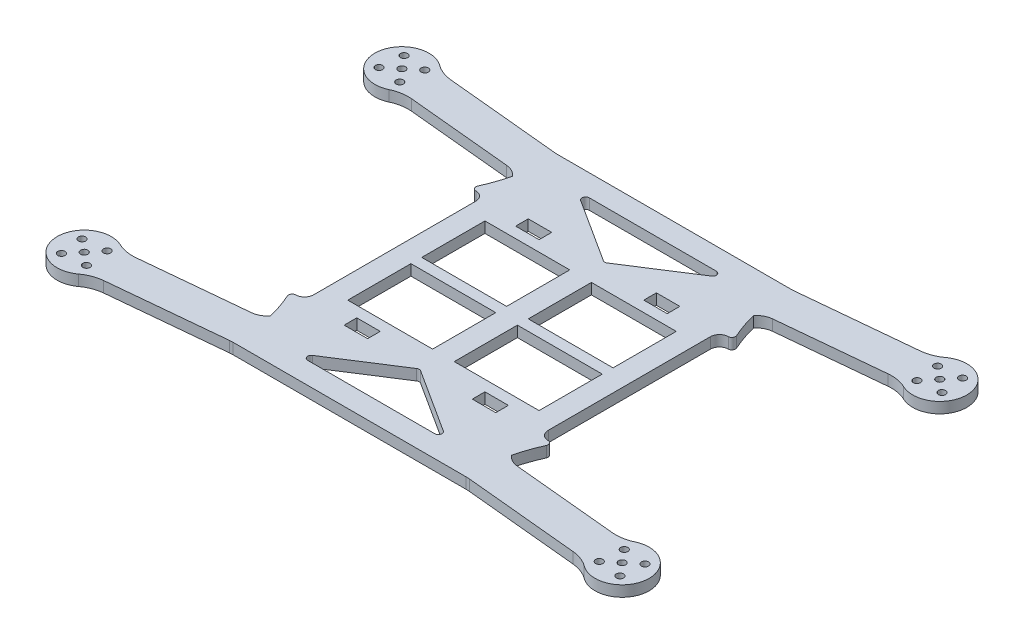
SolidWorks part; units mm, degrees
material "Custom PLA"
ref_plane "Front Plane" through (0, 0, 0) normal (0, 0, 1) x (1, 0, 0)
ref_plane "Top Plane" through (0, 0, 0) normal (0, 1, 0) x (1, 0, 0)
ref_plane "Right Plane" through (0, 0, 0) normal (1, 0, 0) x (0, 0, -1)
sketch "Sketch1" plane through (0, 0, 0) normal (0, 1, 0) x (1, 0, 0)
  line L0 (-101.3207, 0) -> (4964.7124, 0) construction
  line L1 (0, -101.3207) -> (0, 4964.7124) construction
  line L4 (33.2085, 45.046) -> (65.0466, 48.1117)
  line L5 (36.823, 35.3478) -> (66.0089, 38.1581)
  line L6 (0.5402, 25.8595) -> (18.1402, 37.1585)
  line L7 (3, 1.5) -> (26.5, 1.5)
  line L8 (3, 1.5) -> (3, 19)
  line L9 (3, 19) -> (26.5, 19)
  line L10 (26.5, 1.5) -> (26.5, 19)
  line L11 (14.5, 22) -> (21, 22)
  line L12 (14.5, 22) -> (14.5, 25.5)
  line L13 (14.5, 25.5) -> (21, 25.5)
  line L14 (21, 22) -> (21, 25.5)
  line L15 (17.6, 39) -> (-17.6, 39)
  line L16 (-18.1402, 37.1585) -> (-0.5402, 25.8595)
  line L17 (71.6376, 40.5277) -> (71.0277, 46.8624) construction
  line L18 (32.5, 22.45) -> (32.5, -22.45)
  line L30 (32.25, 45) -> (-32.25, 45)
  line L31 (-71.6376, 40.5277) -> (-71.0277, 46.8624) construction
  line L33 (-32.5, 22.45) -> (-32.5, -22.45)
  line L34 (-21, 22) -> (-21, 25.5)
  line L35 (-14.5, 25.5) -> (-21, 25.5)
  line L36 (-14.5, 22) -> (-14.5, 25.5)
  line L37 (-14.5, 22) -> (-21, 22)
  line L38 (-26.5, 1.5) -> (-26.5, 19)
  line L39 (-3, 19) -> (-26.5, 19)
  line L40 (-3, 1.5) -> (-3, 19)
  line L41 (-3, 1.5) -> (-26.5, 1.5)
  line L42 (-36.823, 35.3478) -> (-66.0089, 38.1581)
  line L43 (-33.2085, 45.046) -> (-65.0466, 48.1117)
  line L44 (-71.6376, -40.5277) -> (-71.0277, -46.8624) construction
  line L45 (71.6376, -40.5277) -> (71.0277, -46.8624) construction
  line L46 (-33.2085, -45.046) -> (-65.0466, -48.1117)
  line L47 (-36.823, -35.3478) -> (-66.0089, -38.1581)
  line L48 (-3, -1.5) -> (-26.5, -1.5)
  line L49 (-3, -1.5) -> (-3, -19)
  line L50 (-3, -19) -> (-26.5, -19)
  line L51 (-26.5, -1.5) -> (-26.5, -19)
  line L52 (-14.5, -22) -> (-21, -22)
  line L53 (-14.5, -22) -> (-14.5, -25.5)
  line L54 (-14.5, -25.5) -> (-21, -25.5)
  line L55 (-21, -22) -> (-21, -25.5)
  line L56 (32.25, -45) -> (-32.25, -45)
  line L57 (-18.1402, -37.1585) -> (-0.5402, -25.8595)
  line L58 (17.6, -39) -> (-17.6, -39)
  line L59 (21, -22) -> (21, -25.5)
  line L60 (14.5, -25.5) -> (21, -25.5)
  line L61 (14.5, -22) -> (14.5, -25.5)
  line L62 (14.5, -22) -> (21, -22)
  line L63 (26.5, -1.5) -> (26.5, -19)
  line L64 (3, -19) -> (26.5, -19)
  line L65 (3, -1.5) -> (3, -19)
  line L66 (3, -1.5) -> (26.5, -1.5)
  line L67 (0.5402, -25.8595) -> (18.1402, -37.1585)
  line L68 (36.823, -35.3478) -> (66.0089, -38.1581)
  line L69 (33.2085, -45.046) -> (65.0466, -48.1117)
  arc A0 (34.9643, 24.9497) -> (32.5, 22.45) centre (35, 22.45) ccw
  arc A1 (34.9643, 24.9497) -> (35.8626, 26.3585) centre (34.95, 25.9496) ccw
  arc A2 (35.8626, 26.3585) -> (33.4, 33.497) centre (74.649, 43.7329) cw
  arc A3 (36.823, 35.3478) -> (33.4, 33.497) centre (37.3022, 30.3708) ccw
  arc A4 (71.2717, 37.2303) -> (66.0089, 38.1581) centre (66.9673, 28.2041) ccw
  arc A5 (65.0466, 48.1117) -> (70.0378, 50.0281) centre (64.0881, 58.0657) ccw
  arc A6 (71.2717, 37.2303) -> (70.0378, 50.0281) centre (74.5, 44) ccw
  arc A7 (-17.6, 39) -> (-18.1402, 37.1585) centre (-17.6, 38) ccw
  arc A8 (18.1402, 37.1585) -> (17.6, 39) centre (17.6, 38) ccw
  arc A9 (0.5402, 25.8595) -> (-0.5402, 25.8595) centre (0, 26.701) cw
  circle A10 centre (74.5, 44) radius 1
  circle A11 centre (71.0277, 46.8624) radius 1
  circle A12 centre (77.3624, 47.4723) radius 1
  circle A13 centre (77.9723, 41.1376) radius 1
  circle A14 centre (71.6376, 40.5277) radius 1
  arc A54 (32.25, 45) -> (33.2085, 45.046) centre (32.25, 55) ccw
  arc A55 (-32.25, 45) -> (-33.2085, 45.046) centre (-32.25, 55) cw
  circle A56 centre (-71.6376, 40.5277) radius 1
  circle A57 centre (-77.9723, 41.1376) radius 1
  circle A58 centre (-77.3624, 47.4723) radius 1
  circle A59 centre (-71.0277, 46.8624) radius 1
  circle A60 centre (-74.5, 44) radius 1
  arc A61 (-71.2717, 37.2303) -> (-70.0378, 50.0281) centre (-74.5, 44) cw
  arc A62 (-65.0466, 48.1117) -> (-70.0378, 50.0281) centre (-64.0881, 58.0657) cw
  arc A63 (-71.2717, 37.2303) -> (-66.0089, 38.1581) centre (-66.9673, 28.2041) cw
  arc A64 (-36.823, 35.3478) -> (-33.4, 33.497) centre (-37.3022, 30.3708) cw
  arc A65 (-35.8626, 26.3585) -> (-33.4, 33.497) centre (-74.649, 43.7329) ccw
  arc A66 (-34.9643, 24.9497) -> (-35.8626, 26.3585) centre (-34.95, 25.9496) cw
  arc A67 (-34.9643, 24.9497) -> (-32.5, 22.45) centre (-35, 22.45) cw
  arc A68 (-34.9643, -24.9497) -> (-32.5, -22.45) centre (-35, -22.45) ccw
  arc A69 (-34.9643, -24.9497) -> (-35.8626, -26.3585) centre (-34.95, -25.9496) ccw
  arc A70 (-35.8626, -26.3585) -> (-33.4, -33.497) centre (-74.649, -43.7329) cw
  arc A71 (-36.823, -35.3478) -> (-33.4, -33.497) centre (-37.3022, -30.3708) ccw
  arc A72 (-71.2717, -37.2303) -> (-66.0089, -38.1581) centre (-66.9673, -28.2041) ccw
  arc A73 (-65.0466, -48.1117) -> (-70.0378, -50.0281) centre (-64.0881, -58.0657) ccw
  arc A74 (-71.2717, -37.2303) -> (-70.0378, -50.0281) centre (-74.5, -44) ccw
  circle A75 centre (-74.5, -44) radius 1
  circle A76 centre (-71.0277, -46.8624) radius 1
  circle A77 centre (-77.3624, -47.4723) radius 1
  circle A78 centre (-77.9723, -41.1376) radius 1
  circle A79 centre (-71.6376, -40.5277) radius 1
  arc A80 (-32.25, -45) -> (-33.2085, -45.046) centre (-32.25, -55) ccw
  arc A81 (32.25, -45) -> (33.2085, -45.046) centre (32.25, -55) cw
  circle A82 centre (71.6376, -40.5277) radius 1
  circle A83 centre (77.9723, -41.1376) radius 1
  circle A84 centre (77.3624, -47.4723) radius 1
  circle A85 centre (71.0277, -46.8624) radius 1
  circle A86 centre (74.5, -44) radius 1
  arc A87 (0.5402, -25.8595) -> (-0.5402, -25.8595) centre (0, -26.701) ccw
  arc A88 (18.1402, -37.1585) -> (17.6, -39) centre (17.6, -38) cw
  arc A89 (-17.6, -39) -> (-18.1402, -37.1585) centre (-17.6, -38) cw
  arc A90 (71.2717, -37.2303) -> (70.0378, -50.0281) centre (74.5, -44) cw
  arc A91 (65.0466, -48.1117) -> (70.0378, -50.0281) centre (64.0881, -58.0657) cw
  arc A92 (71.2717, -37.2303) -> (66.0089, -38.1581) centre (66.9673, -28.2041) cw
  arc A93 (36.823, -35.3478) -> (33.4, -33.497) centre (37.3022, -30.3708) cw
  arc A94 (35.8626, -26.3585) -> (33.4, -33.497) centre (74.649, -43.7329) ccw
  arc A95 (34.9643, -24.9497) -> (35.8626, -26.3585) centre (34.95, -25.9496) cw
  arc A96 (34.9643, -24.9497) -> (32.5, -22.45) centre (35, -22.45) cw
  point P15 (32.5, 0)
  point P37 (0, 25.5127)
  point P43 (35.6328, 35.2332)
  point P50 (74.5, 44)
  point P51 (0, 0)
  point P52 (32.7093, 25.9917)
  point P53 (32.7093, 23.4332)
  point P58 (36.1652, 35.2845)
  point P59 (34.916, 25.8595)
  point P60 (33.2085, 33.1307)
  point P89 (0, 45)
  point P98 (-74.5, 44)
  point P172 (-32.5, 0)
  point P180 (-74.5, -44)
  point P181 (0, -45)
  point P182 (74.5, -44)
  point P183 (0, -25.5127)
  dimension "D2" = 2.5
  dimension "D3" = 1
  dimension "D5" = 42.5
  dimension "D6" = 5
  dimension "D7" = 10
  dimension "D8" = 7.5
  dimension "D9" = 149
  dimension "D10" = 88
  dimension "D16" = 14.5
  dimension "D18" = 1
  dimension "D30" = 2
  dimension "D11" = 10
  dimension "D22" = 6
  dimension "D4" = 174.5
  dimension "D12" = 32.5
  dimension "D13" = 10
  dimension "D14" = 64.5
  dimension "D15" = 6.5
  dimension "D17" = 3
  dimension "D19" = 35.2
  dimension "D20" = 32.7
  dimension "D21" = 23.5
  dimension "D23" = 6
  dimension "D24" = 1.5
  dimension "D25" = 45
  dimension "D26" = 0.9
  dimension "D27" = 3.5
  dimension "D28" = 22
  dimension "D29" = 22.45
  dimension "D31" = 4.5
  dimension "D33" = 2.45
  dimension "D32" = 4
extrude "Boss-Extrude1" add sketch "Sketch1" along normal mid plane 3
